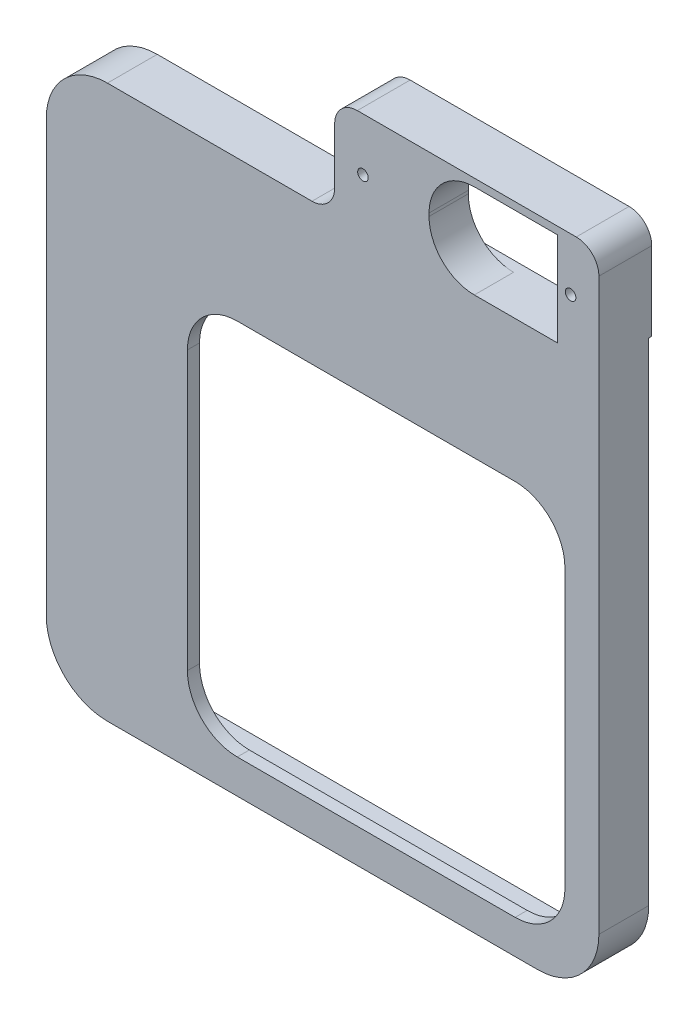
SolidWorks part; units mm, degrees
ref_plane "Front Plane" through (0, 0, 0) normal (0, 0, 1) x (1, 0, 0)
ref_plane "Top Plane" through (0, 0, 0) normal (0, 1, 0) x (1, 0, 0)
ref_plane "Right Plane" through (0, 0, 0) normal (1, 0, 0) x (0, 0, -1)
sketch "Sketch1" plane through (0, 0, 0) normal (0, 0, 1) x (1, 0, 0)
  line L1 (0, 0) -> (70.2, 0)
  line L2 (0, 0) -> (0, 70.2)
  line L3 (0, 70.2) -> (70.2, 70.2)
  line L4 (70.2, 0) -> (70.2, 70.2)
  line L5 (71.7, 71.7) -> (-1.5, 71.7)
  line L6 (71.7, 71.7) -> (71.7, -1.5)
  line L7 (71.7, -1.5) -> (-1.5, -1.5)
  line L8 (-1.5, 71.7) -> (-1.5, -1.5)
  dimension "D1" = 70.2
  dimension "D2" = 70.2
  dimension "D3" = 1.5
  dimension "D4" = 1.5
  dimension "D5" = 1.5
  dimension "D6" = 1.5
extrude "Boss-Extrude1" add sketch "Sketch1" along normal blind 5
sketch "Sketch2" plane through (0, 0, 5) normal (0, 0, 1) x (1, 0, 0)
  line L1 (-1.5, 71.7) -> (71.7, 71.7)
  line L2 (-1.5, 71.7) -> (-1.5, -1.5)
  line L3 (-1.5, -1.5) -> (71.7, -1.5)
  line L4 (71.7, 71.7) -> (71.7, -1.5)
extrude "Boss-Extrude2" add sketch "Sketch2" along normal blind 1.6
fillet "Fillet1" radius 6.6 4 edges at (70.2, 0, 2.5) (0, 0, 2.5) (0, 70.2, 2.5) (70.2, 70.2, 2.5)
sketch "Sketch3" plane through (0, 0, 5) normal (0, 0, -1) x (-1, 0, 0)
  line L0 (-6.6, 0) -> (-63.6, 0) construction
  line L1 (-67.2, 53) -> (-17.2, 53)
  line L2 (-67.2, 53) -> (-67.2, 3)
  line L3 (-67.2, 3) -> (-17.2, 3)
  line L4 (-17.2, 53) -> (-17.2, 3)
  line L5 (-70.2, 6.6) -> (-70.2, 63.6) construction
  dimension "D1" = 50
  dimension "D2" = 50
  dimension "D3" = 3
  dimension "D4" = 3
extrude "Cut-Extrude1" cut sketch "Sketch3" against normal blind 1.6
fillet "Fillet2" radius 6.6 4 edges at (17.2, 3, 5.8) (17.2, 53, 5.8) (67.2, 53, 5.8) (67.2, 3, 5.8)
sketch "Sketch5" plane through (0, 0, 6.6) normal (0, 0, 1) x (1, 0, 0)
  line L1 (71.7, 71.7) -> (36.7, 71.7)
  line L2 (71.7, 71.7) -> (71.7, 84.1)
  line L3 (71.7, 84.1) -> (36.7, 84.1)
  line L4 (36.7, 71.7) -> (36.7, 84.1)
  dimension "D1" = 35
  dimension "D2" = 12.4
extrude "Boss-Extrude3" add sketch "Sketch5" against normal blind 7
sketch "Sketch6" plane through (0, 0, -0.4) normal (0, 0, -1) x (-1, 0, 0)
  line L0 (-36.7, 71.7) -> (-71.7, 71.7) construction
  line L1 (-42.2, 71.7) -> (-66.2, 71.7)
  line L2 (-42.2, 71.7) -> (-42.2, 84.1)
  line L3 (-42.2, 84.1) -> (-66.2, 84.1)
  line L4 (-66.2, 71.7) -> (-66.2, 84.1)
  line L5 (-71.7, 84.1) -> (-36.7, 84.1) construction
  line L6 (-71.7, 71.7) -> (-71.7, 84.1) construction
  line L7 (-36.7, 84.1) -> (-36.7, 71.7) construction
  point P8 (-71.7, 77.9)
  point P11 (-36.7, 77.9)
  dimension "D1" = 5.5
  dimension "D2" = 5.5
extrude "Cut-Extrude2" cut sketch "Sketch6" against normal blind 1.8
sketch "Sketch7" plane through (0, 0, 1.4) normal (0, 0, -1) x (-1, 0, 0)
  line L0 (-42.2, 84.1) -> (-66.2, 84.1) construction
  line L1 (-66.2, 71.7) -> (-49.2, 71.7)
  line L2 (-66.2, 71.7) -> (-66.2, 84.1)
  line L3 (-66.2, 84.1) -> (-49.2, 84.1)
  line L4 (-49.2, 71.7) -> (-49.2, 84.1)
  dimension "D1" = 17
extrude "Cut-Extrude3" cut sketch "Sketch7" against normal blind 10.8
sketch "Sketch8" plane through (0, 84.1, 0) normal (0, 1, 0) x (1, 0, 0)
  line L1 (36.7, 0.4) -> (71.7, 0.4)
  line L2 (36.7, 0.4) -> (36.7, -6.6)
  line L3 (36.7, -6.6) -> (71.7, -6.6)
  line L4 (71.7, 0.4) -> (71.7, -6.6)
extrude "Boss-Extrude4" add sketch "Sketch8" along normal blind 1
fillet "Fillet3" radius 8.1 3 edges at (71.7, -1.5, 3.3) (-1.5, -1.5, 3.3) (-1.5, 71.7, 3.3)
fillet "Fillet4" radius 3 3 edges at (71.7, 85.1, 3.1) (36.7, 85.1, 3.1)
fillet "Fillet5" radius 6 2 edges at (49.2, 84.1, 4) (49.2, 71.7, 4)
sketch "Sketch9" plane through (0, 0, -0.4) normal (0, 0, -1) x (-1, 0, 0)
  circle A0 centre (-40.4488, 78.1) radius 0.7
  circle A1 centre (-67.9488, 78.1) radius 0.7
  dimension "D1" = 1.4
  dimension "D2" = 1.4
extrude "Cut-Extrude4" cut sketch "Sketch9" against normal blind 10
